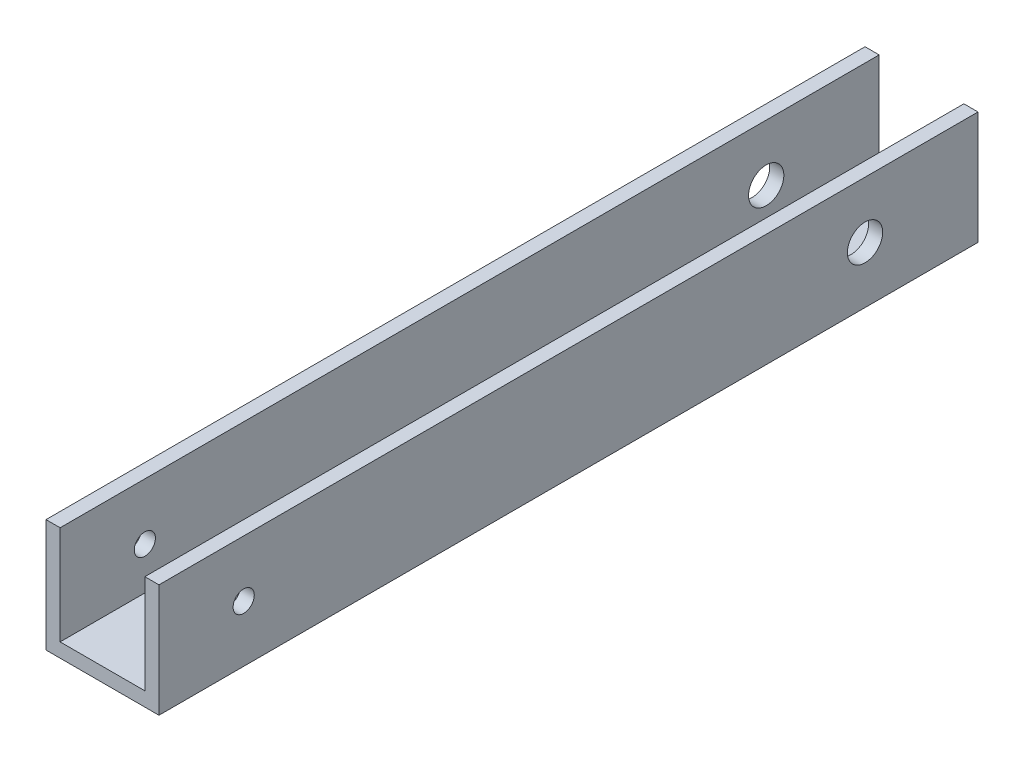
SolidWorks part; units mm, degrees
ref_plane "Front Plane" through (0, 0, 0) normal (0, 0, 1) x (1, 0, 0)
ref_plane "Top Plane" through (0, 0, 0) normal (0, 1, 0) x (1, 0, 0)
ref_plane "Right Plane" through (0, 0, 0) normal (1, 0, 0) x (0, 0, -1)
sketch "Sketch1" plane through (0, 0, 0) normal (0, 0, 1) x (1, 0, 0)
  line L0 (0, 0) -> (25.4, 0)
  line L1 (25.4, 0) -> (25.4, 25.4)
  line L2 (25.4, 25.4) -> (22.225, 25.4)
  line L3 (22.225, 25.4) -> (22.225, 3.175)
  line L4 (22.225, 3.175) -> (3.175, 3.175)
  line L5 (3.175, 3.175) -> (3.175, 25.4)
  line L6 (3.175, 25.4) -> (0, 25.4)
  line L7 (0, 25.4) -> (0, 0)
  dimension "D1" = 3.175
  dimension "D2" = 3.175
  dimension "D3" = 3.175
  dimension "D4" = 25.4
  dimension "D5" = 25.4
  dimension "D6" = 25.4
extrude "Boss-Extrude1" add sketch "Sketch1" along normal blind 184.15
sketch "Sketch2" plane through (25.4, 0, 0) normal (1, 0, 0) x (0, 0, -1)
  line L2 (-184.15, 25.4) -> (0, 25.4) construction
  line L3 (-184.15, 0) -> (-184.15, 25.4) construction
  circle A0 centre (-165.1, 12.7) radius 2.3813
  circle A1 centre (-25.4, 12.7) radius 3.9687
  point P6 (-184.15, 12.7)
  dimension "D1" = 4.7625
  dimension "D3" = 139.7
  dimension "D5" = 7.9375
  dimension "D2" = 12.7
  dimension "D4" = 19.05
extrude "Cut-Extrude1" cut sketch "Sketch2" against normal blind 25.4
